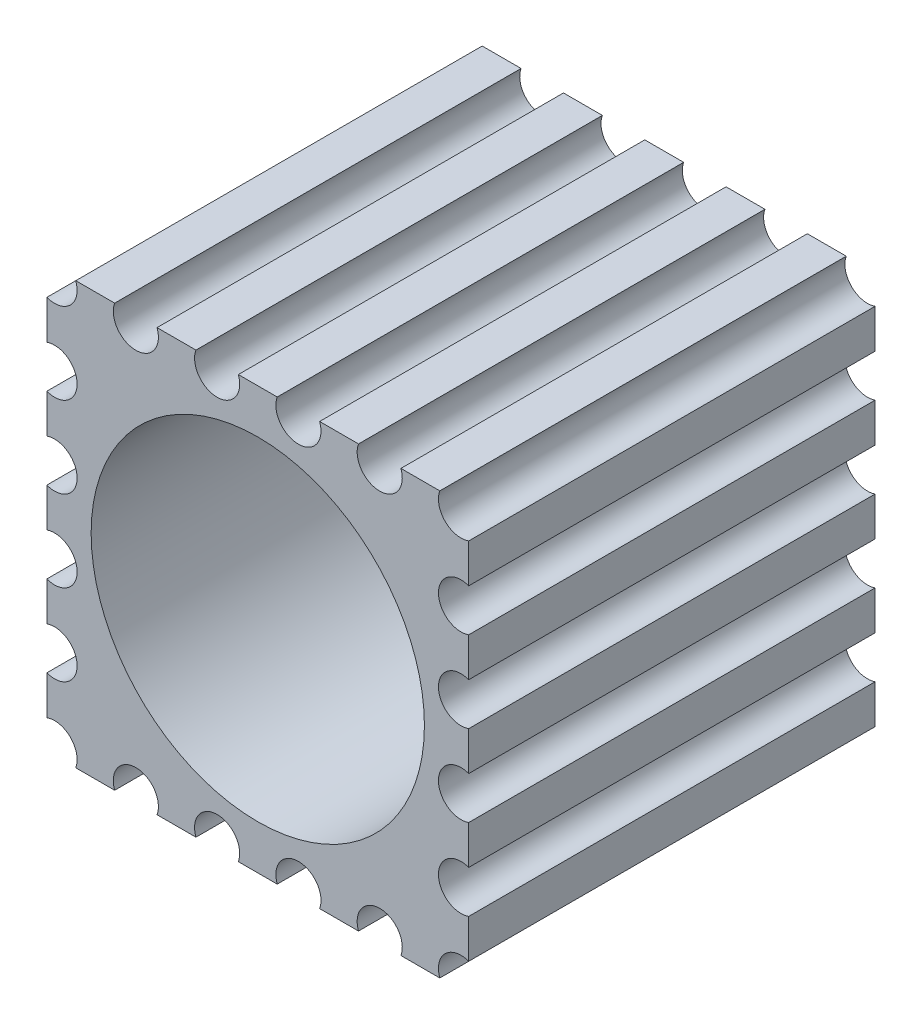
SolidWorks part; units mm, degrees
ref_plane "Front Plane" through (0, 0, 0) normal (0, 0, 1) x (1, 0, 0)
ref_plane "Top Plane" through (0, 0, 0) normal (0, 1, 0) x (1, 0, 0)
ref_plane "Right Plane" through (0, 0, 0) normal (1, 0, 0) x (0, 0, -1)
sketch "Sketch2" plane through (0, 0, 0) normal (0, 0, 1) x (1, 0, 0)
  line L0 (-8.1984, 4.754) -> (1.8016, -5.246) construction
  line L1 (-7.6769, 4.944) -> (-6.7198, 4.944)
  line L2 (-8.3884, 4.2325) -> (-8.3884, 3.2754)
  line L3 (-7.6769, -5.436) -> (-6.7198, -5.436)
  line L4 (1.9916, 4.2325) -> (1.9916, 3.2754)
  line L9 (-7.8059, -4.8536) -> (1.8016, 4.754) construction
  line L10 (-5.6769, 4.944) -> (-4.7198, 4.944)
  line L11 (-3.6769, 4.944) -> (-2.7198, 4.944)
  line L12 (-1.6769, 4.944) -> (-0.7198, 4.944)
  line L13 (0.3231, 4.944) -> (1.2802, 4.944)
  line L14 (1.9916, 2.2325) -> (1.9916, 1.2754)
  line L15 (1.9916, 0.2325) -> (1.9916, -0.7246)
  line L16 (1.9916, -1.7675) -> (1.9916, -2.7246)
  line L17 (1.9916, -3.7675) -> (1.9916, -4.7246)
  line L18 (0.3231, -5.436) -> (1.2802, -5.436)
  line L19 (-1.6769, -5.436) -> (-0.7198, -5.436)
  line L20 (-3.6769, -5.436) -> (-2.7198, -5.436)
  line L21 (-5.6769, -5.436) -> (-4.7198, -5.436)
  line L22 (-8.3884, -3.7675) -> (-8.3884, -4.7246)
  line L23 (-8.3884, -1.7675) -> (-8.3884, -2.7246)
  line L24 (-8.3884, 0.2325) -> (-8.3884, -0.7246)
  line L25 (-8.3884, 2.2325) -> (-8.3884, 1.2754)
  arc A0 (-8.3884, 4.2325) -> (-7.6769, 4.944) centre (-8.1984, 4.754) ccw
  arc A1 (-6.7198, 4.944) -> (-5.6769, 4.944) centre (-6.1984, 4.754) ccw
  arc A2 (-4.7198, 4.944) -> (-3.6769, 4.944) centre (-4.1984, 4.754) ccw
  arc A3 (-2.7198, 4.944) -> (-1.6769, 4.944) centre (-2.1984, 4.754) ccw
  arc A4 (-0.7198, 4.944) -> (0.3231, 4.944) centre (-0.1984, 4.754) ccw
  arc A5 (1.2802, 4.944) -> (1.9916, 4.2325) centre (1.8016, 4.754) ccw
  arc A6 (1.9916, 3.2754) -> (1.9916, 2.2325) centre (1.8016, 2.754) ccw
  arc A7 (1.9916, 1.2754) -> (1.9916, 0.2325) centre (1.8016, 0.754) ccw
  arc A8 (1.9916, -0.7246) -> (1.9916, -1.7675) centre (1.8016, -1.246) ccw
  arc A9 (1.9916, -2.7246) -> (1.9916, -3.7675) centre (1.8016, -3.246) ccw
  arc A10 (1.9916, -4.7246) -> (1.2802, -5.436) centre (1.8016, -5.246) ccw
  arc A11 (0.3231, -5.436) -> (-0.7198, -5.436) centre (-0.1984, -5.246) ccw
  arc A12 (-1.6769, -5.436) -> (-2.7198, -5.436) centre (-2.1984, -5.246) ccw
  arc A13 (-3.6769, -5.436) -> (-4.7198, -5.436) centre (-4.1984, -5.246) ccw
  arc A14 (-5.6769, -5.436) -> (-6.7198, -5.436) centre (-6.1984, -5.246) ccw
  arc A15 (-7.6769, -5.436) -> (-8.3884, -4.7246) centre (-8.1984, -5.246) ccw
  arc A16 (-8.3884, -3.7675) -> (-8.3884, -2.7246) centre (-8.1984, -3.246) ccw
  arc A17 (-8.3884, -1.7675) -> (-8.3884, -0.7246) centre (-8.1984, -1.246) ccw
  arc A18 (-8.3884, 0.2325) -> (-8.3884, 1.2754) centre (-8.1984, 0.754) ccw
  arc A19 (-8.3884, 2.2325) -> (-8.3884, 3.2754) centre (-8.1984, 2.754) ccw
  circle A20 centre (-3.1984, -0.246) radius 4.1
  circle A21 centre (-3.1984, -0.246) radius 2.6
  dimension "D7" = 6
  dimension "D8" = 6
  dimension "D9" = 6
  dimension "D10" = 5
extrude "Boss-Extrude2" add sketch "Sketch2" along normal blind 10 contours A19 L25 A18 L24 A17 L23 A16 L22 A15 L3 A14 L21 A13 L20 A12 L19 A11 L18 A10 L17 A9 L16 A8 L15 A7 L14 A6 L4 A5 L13 A4 L12 A3 L11 A2 L10 A1 L1 A0 L2 A20
